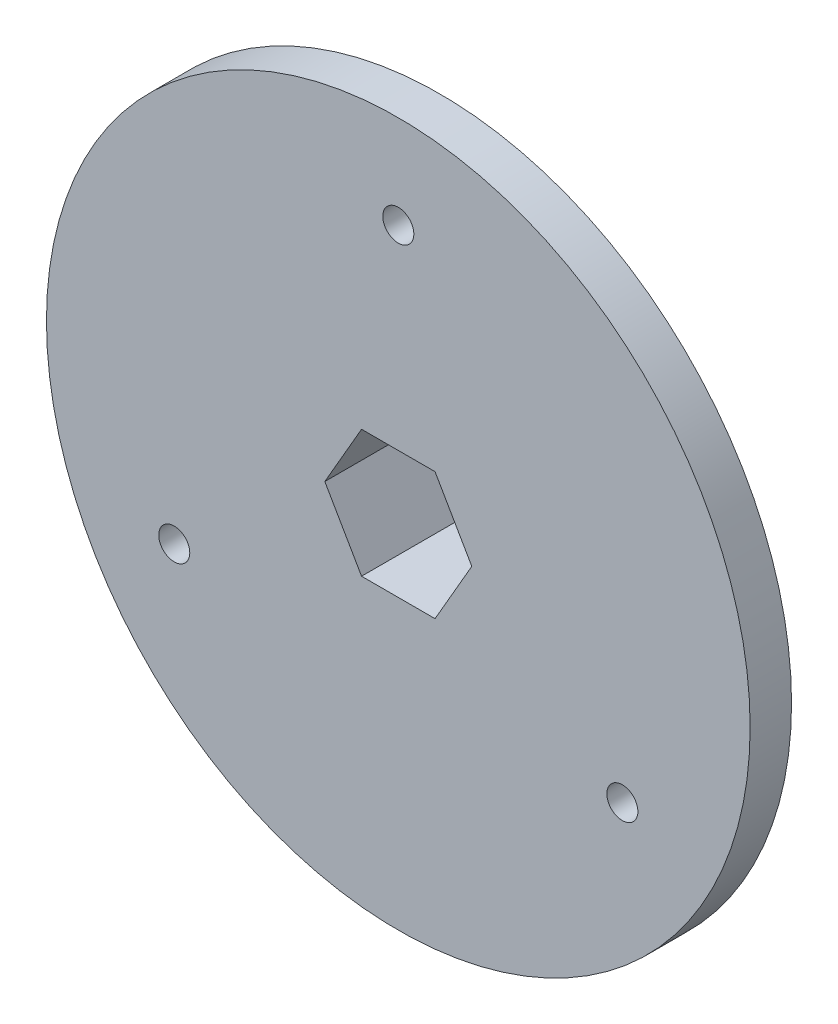
SolidWorks part; units mm, degrees
ref_plane "Alzado" through (0, 0, 0) normal (0, 0, 1) x (1, 0, 0)
ref_plane "Planta" through (0, 0, 0) normal (0, 1, 0) x (1, 0, 0)
ref_plane "Vista lateral" through (0, 0, 0) normal (1, 0, 0) x (0, 0, -1)
sketch "Croquis1" plane through (0, 0, 0) normal (0, 0, 1) x (1, 0, 0)
  line L0 (0, 15.6083) -> (0, -18.3127) construction
  line L1 (0, 0) -> (0, 25) construction
  circle A0 centre (0, 0) radius 34
  circle A1 centre (0, 0) radius 25 construction
  circle A2 centre (0, 25) radius 1.5
  circle A3 centre (21.6506, -12.5) radius 1.5
  circle A4 centre (-21.6506, -12.5) radius 1.5
  dimension "D1" = 68
  dimension "D2" = 3
  dimension "D3" = 50
  dimension "D4" = 3
extrude "Saliente-Extruir1" add sketch "Croquis1" along normal blind 4
sketch "Croquis2" plane through (0, 0, 0) normal (0, 0, -1) x (-1, 0, 0)
  line L1 (3.5507, 6.15) -> (-3.5507, 6.15)
  line L2 (-3.5507, 6.15) -> (-7.1014, 0)
  line L3 (-7.1014, 0) -> (-3.5507, -6.15)
  line L4 (-3.5507, -6.15) -> (3.5507, -6.15)
  line L5 (3.5507, -6.15) -> (7.1014, 0)
  line L6 (7.1014, 0) -> (3.5507, 6.15)
  circle A0 centre (0, 0) radius 6.15 construction
  dimension "D1" = 12.3
extrude "Cortar-Extruir1" cut sketch "Croquis2" against normal blind 4
sketch "Croquis3" plane through (0, 0, 0) normal (0, 0, -1) x (-1, 0, 0)
  line L0 (-7.1014, 0) -> (-3.5507, -6.15) construction
  line L1 (-3.5507, -6.15) -> (3.5507, -6.15) construction
  line L2 (3.5507, -6.15) -> (7.1014, 0) construction
  line L3 (7.1014, 0) -> (3.5507, 6.15) construction
  line L4 (3.5507, 6.15) -> (-3.5507, 6.15) construction
  line L5 (-3.5507, 6.15) -> (-7.1014, 0) construction
  line L6 (-7.1014, 0) -> (-3.5507, -6.15)
  line L7 (-3.5507, -6.15) -> (3.5507, -6.15)
  line L8 (3.5507, -6.15) -> (7.1014, 0)
  line L9 (7.1014, 0) -> (3.5507, 6.15)
  line L10 (3.5507, 6.15) -> (-3.5507, 6.15)
  line L11 (-3.5507, 6.15) -> (-7.1014, 0)
  circle A0 centre (0, 0) radius 9
  circle A1 centre (0, 0) radius 34
  circle A2 centre (0, 0) radius 34
  line M8 (-3.5507, 6.15) -> (3.5507, 6.15)
  line M9 (3.5507, 6.15) -> (7.1014, 0)
  line M10 (7.1014, 0) -> (3.5507, -6.15)
  line M11 (3.5507, -6.15) -> (-3.5507, -6.15)
  line M12 (-3.5507, -6.15) -> (-7.1014, 0)
  line M13 (-7.1014, 0) -> (-3.5507, 6.15)
  circle M15 centre (0, 25) radius 1.5
  circle M16 centre (-21.6506, -12.5) radius 1.5
  circle M17 centre (21.6506, -12.5) radius 1.5
  dimension "D2" = 18
  dimension "D1" = 0
extrude "Saliente-Extruir2" add sketch "Croquis3" along normal blind 6 contours A0 M15 M16 M17 M13 M8 M9 M10 M11 M12
sketch "Croquis4" plane through (0, 0, 0) normal (0, 1, 0) x (1, 0, 0)
  line L0 (9, 6) -> (9, 0)
  line L1 (9, 0) -> (16.9623, 0)
  line L2 (34, 0) -> (-34, 0) construction
  line L3 (16.9623, 0) -> (9, 6)
  line L4 (0, 12.7599) -> (0, -10.6416) construction
  dimension "D1" = 37
revolve "Revolución1" add sketch "Croquis4" angle 360 about L4
